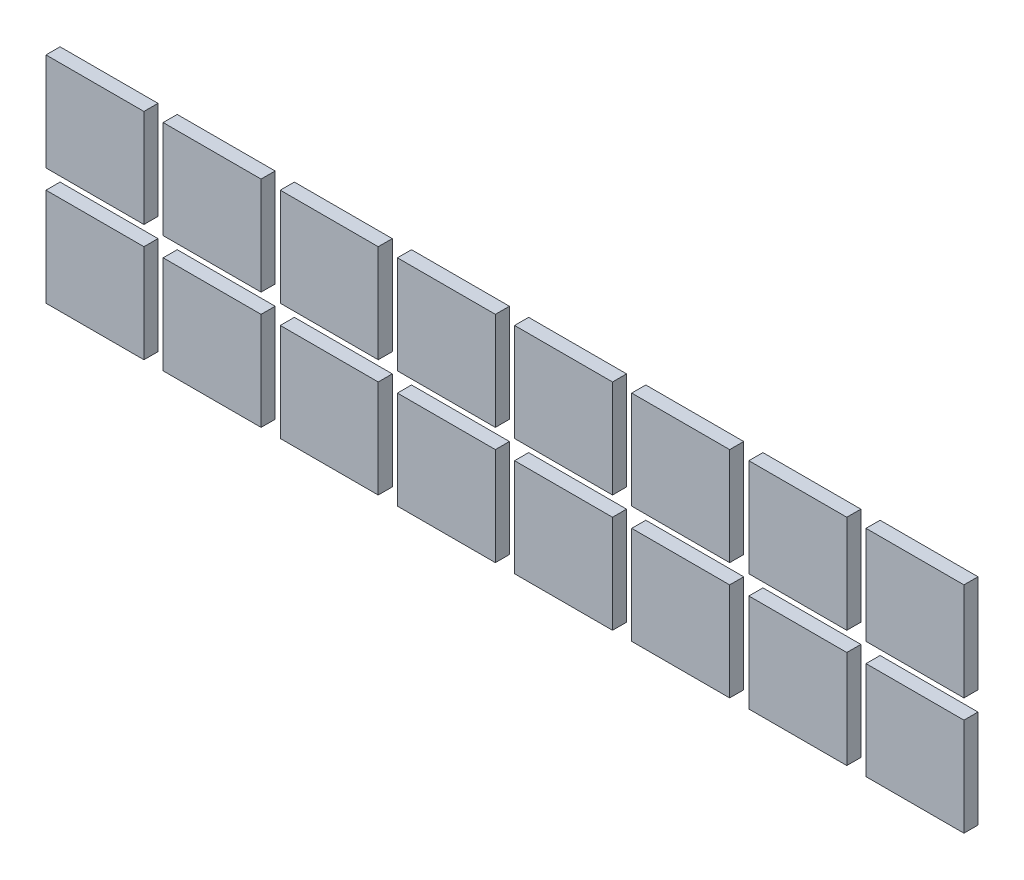
SolidWorks part; units mm, degrees
ref_plane "Front Plane" through (0, 0, 0) normal (1, 0, 0) x (0, 1, 0)
ref_plane "Top Plane" through (0, 0, 0) normal (0, 0, 1) x (0, 1, 0)
ref_plane "Right Plane" through (0, 0, 0) normal (0, 1, 0) x (-1, 0, 0)
sketch "Sketch1" plane through (0, 0, 0) normal (0, 0, 1) x (0, 1, 0)
  line L1 (0, 0) -> (20.9, 0)
  line L2 (0, 0) -> (0, 20.9)
  line L3 (0, 20.9) -> (20.9, 20.9)
  line L4 (20.9, 0) -> (20.9, 20.9)
  dimension "D1" = 20.9
  dimension "D2" = 20.9
extrude "Boss-Extrude1" add sketch "Sketch1" along normal blind 3
sketch "Sketch2" plane through (0, 0, 0) normal (0, 0, -1) x (1, 0, 0)
  line L0 (-20.9, 0) -> (0, -20.9) construction
  circle A0 centre (-10.45, -10.45) radius 7.56
  dimension "D1" = 15.12
extrude "Cut-Extrude1" cut sketch "Sketch2" against normal blind 2
pattern_linear "LPattern1" count 8 spacing 25 along (-1, 0, 0) count 2 spacing 25 along (0, -1, 0) of bodies 102
